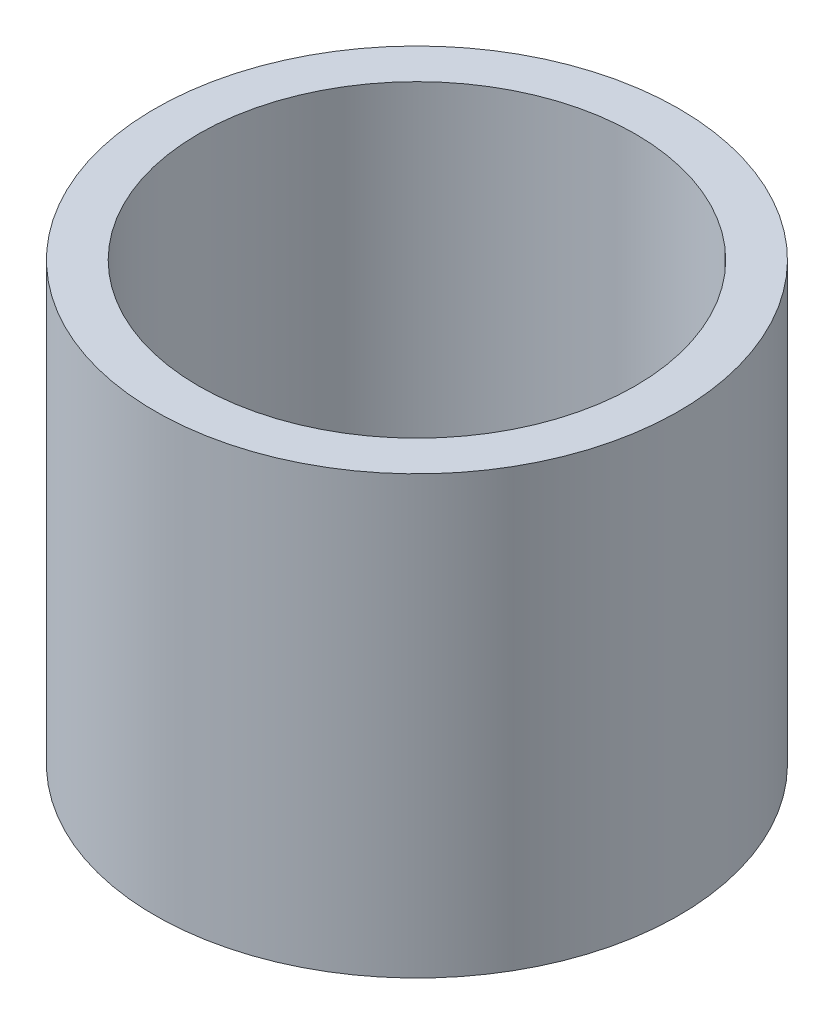
SolidWorks part; units mm, degrees
material "PVC Rigid"
ref_plane "Front Plane" through (0, 0, 0) normal (0, 0, 1) x (1, 0, 0)
ref_plane "Top Plane" through (0, 0, 0) normal (0, 1, 0) x (1, 0, 0)
ref_plane "Right Plane" through (0, 0, 0) normal (1, 0, 0) x (0, 0, -1)
sketch "Sketch1" plane through (0, 0, 0) normal (0, 1, 0) x (1, 0, 0)
  circle A0 centre (0, 0) radius 11.43
  circle A1 centre (0, 0) radius 9.525
  dimension "D1" = 1.905
  dimension "D2" = 19.05
extrude "Boss-Extrude1" add sketch "Sketch1" along normal blind 19.05
